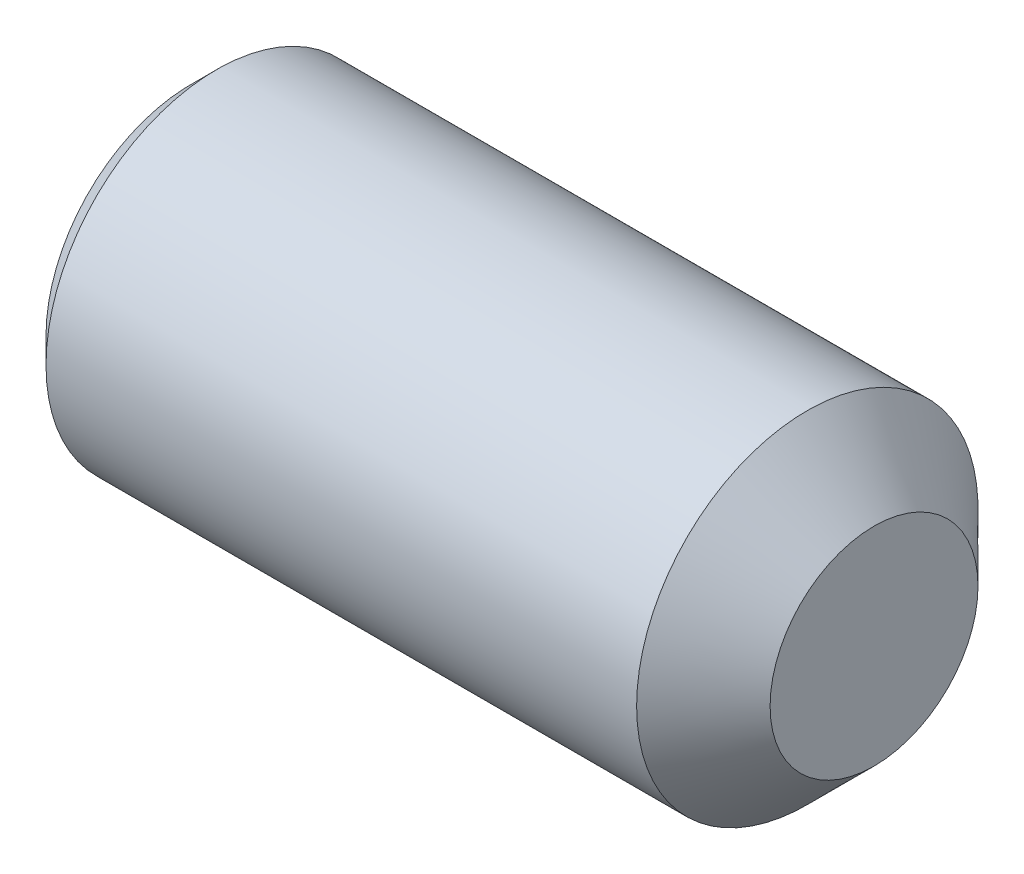
SolidWorks part; units mm, degrees
revolve "BaseBody" add sketch "BodySke" angle 360 about L5
sketch "BodySke" plane through (0, 0, 0) normal (0, 0, 1) x (1, 0, 0)
  line L0 (0, 0) -> (0, 10.8102)
  line L1 (0, 10.8102) -> (1.8898, 12.7)
  line L2 (1.8898, 12.7) -> (45.8343, 12.7)
  line L3 (45.8343, 12.7) -> (50.8, 7.7343)
  line L4 (50.8, 0) -> (0, 0)
  line L5 (-12.7, 0) -> (88.9, 0) construction
  line L6 (50.8, 7.7343) -> (50.8, 0)
  line L7 (50.8, 7.7343) -> (50.8, 17.2593) construction
  line L8 (0, -10.8102) -> (1.8898, -12.7) construction
  line L9 (2.1082, 15.875) -> (2.1082, -3.175) construction
  line L10 (45.8343, -12.7) -> (50.8, -7.7343) construction
  dimension "Diameter" = 25.4
  dimension "Drive_ch_ang" = 45
  dimension "Minor_dia" = 21.6205
  dimension "Cup_nose_ang" = 45
  dimension "Cup_dia" = 15.4686
  dimension "Length" = 50.8
  dimension "Advance" = 2.1082
cosmetic thread "ThreadCosmetic" [suppressed] parameters "Thread_minor"=21.6205
ref_plane "Plane1" through (0, 0, 0) normal (0, 0, 1) x (1, 0, 0)
ref_plane "Plane2" through (0, 0, 0) normal (0, 1, 0) x (1, 0, 0)
ref_plane "Plane3" through (0, 0, 0) normal (1, 0, 0) x (0, 0, -1)
sketch "Sketch2" plane through (0, 0, 0) normal (-1, 0, 0) x (0, 0, 1)
  line L0 (4.1208, 7.1374) -> (-4.1208, 7.1374)
  line L1 (-4.1208, 7.1374) -> (-8.2416, 0)
  line L2 (4.1208, 7.1374) -> (8.2416, 0)
  line L3 (4.1208, -7.1374) -> (8.2416, 0)
  line L4 (4.1208, -7.1374) -> (-4.1208, -7.1374)
  line L5 (-4.1208, -7.1374) -> (-8.2416, 0)
  dimension "Hex_size" = 14.2748
  dimension "D2" = 7.1374
  dimension "D3" = 7.1374
extrude "Hex" cut sketch "Sketch2" against normal blind 14.2748
sketch "Sketch4" plane through (0, 4.7709, -0.5249) normal (-1, 0, 0) x (0, 0, 1)
  line L0 (0.5249, -4.7709) -> (10.6976, -4.7709)
  line L1 (0.5249, -4.7709) -> (6.6732, -1.2211) construction
  line L2 (0.5249, -4.7709) -> (5.6112, 4.0389)
  line L3 (8.9666, -2.6687) -> (10.2861, -1.9069)
  line L4 (6.5663, 1.4888) -> (7.8858, 2.2506)
  arc A0 (8.9666, -2.6687) -> (6.5663, 1.4888) centre (0.5249, -4.7709) ccw
  arc A1 (10.6976, -4.7709) -> (10.2861, -1.9069) centre (0.5249, -4.7709) ccw
  arc A2 (5.6112, 4.0389) -> (7.8858, 2.2506) centre (0.5249, -4.7709) cw
  circle A3 centre (0.5249, -4.7709) radius 8.6995 construction
  circle A4 centre (0.5249, -4.7709) radius 10.1727 construction
  dimension "Spline_n_dim" = 17.399
  dimension "Spline_m_dim" = 20.3454
  dimension "D1" = 30
  dimension "Spline_a_dim" = 60
  dimension "Spline_p_dim" = 4.8006
  dimension "D3" = 2.4003
extrude "Spline" [suppressed] cut sketch "Sketch4" against normal blind 12.7
pattern_circular "CirPattern1" [suppressed] count 6 every 60 about axis through (-12.7, 0, 0) along (1, 0, 0)
sketch "ThdSchSke" plane through (0, 0, 0) normal (0, 0, 1) x (1, 0, 0)
  line L0 (1.8898, -10.8102) -> (0.5665, -12.7)
  line L1 (1.8898, -10.8102) -> (3.213, -12.7)
  line L2 (3.213, -12.7) -> (3.213, -15.875)
  line L3 (-3.175, 0) -> (5.1513, 0) construction
  line L4 (1.8898, 12.7) -> (1.8898, -12.7) construction
  line L5 (3.213, -15.875) -> (0.5665, -15.875)
  line L6 (0.5665, -15.875) -> (0.5665, -12.7)
  dimension "Thread_minor" = 21.6205
  dimension "Diameter" = 25.4
revolve "ThreadSchematic" [suppressed] cut sketch "ThdSchSke" angle 360 about L3
pattern_linear "ThdSchPat" [suppressed]
equation "\"D2@Sketch2\" = \"Hex_size@Sketch2\" / 2"
equation "\"D3@Sketch2\" = \"Hex_size@Sketch2\" / 2"
equation "\"Thread_minor@ThreadCosmetic\" = \"Minor_dia@BodySke\""
equation "\"D1@Sketch4\" = \"Spline_a_dim@Sketch4\" / 2"
equation "\"D3@Sketch4\" = \"Spline_p_dim@Sketch4\" / 2"
equation "\"D2@CirPattern1\" = \"Spline_a_dim@Sketch4\""
equation "\"Num_teeth@CirPattern1\" = 360 / \"D2@CirPattern1\""
equation "\"Thread_minor@ThdSchSke\" = \"Thread_minor@ThreadCosmetic\""
equation "\"Diameter@ThdSchSke\" = \"Diameter@BodySke\""
equation "\"Overcut@ThdSchSke\" = \"Diameter@BodySke\" * 1.25"
equation "\"Num_threads@ThdSchPat\" = int( (\"Length@BodySke\" - ( ( ( \"Diameter@BodySke\" - \"Minor_dia@BodySke\" ) * 0.5 ) / tan( \"Drive_ch_ang@BodySke\" * 0.017453292 ) ) - ( ( ( \"Diameter@BodySke\" - \"Cup_dia@BodySke\" ) * 0.5 ) * tan( \"Cup_nose_ang@BodySke\" * 0.017453292 ) ) ) / \"Advance@BodySke\" + 0.999 )  + 1"
equation "\"Advance@ThdSchPat\" = (\"Length@BodySke\" - ( ( ( \"Diameter@BodySke\" - \"Minor_dia@BodySke\" ) * 0.5 ) / tan( \"Drive_ch_ang@BodySke\" * 0.017453292 ) ) - ( ( ( \"Diameter@BodySke\" - \"Cup_dia@BodySke\" ) * 0.5 ) * tan( \"Cup_nose_ang@BodySke\" * 0.017453292 ) ) ) /  (\"Num_threads@ThdSchPat\" - 1) 'relax it"
equation "' \"Num_threads@ThdSchPat\" = \"Num_threads@ThdSchPat\" - sgn( \"Num_threads@ThdSchPat\" - 1) '---chamfered tips only---"
